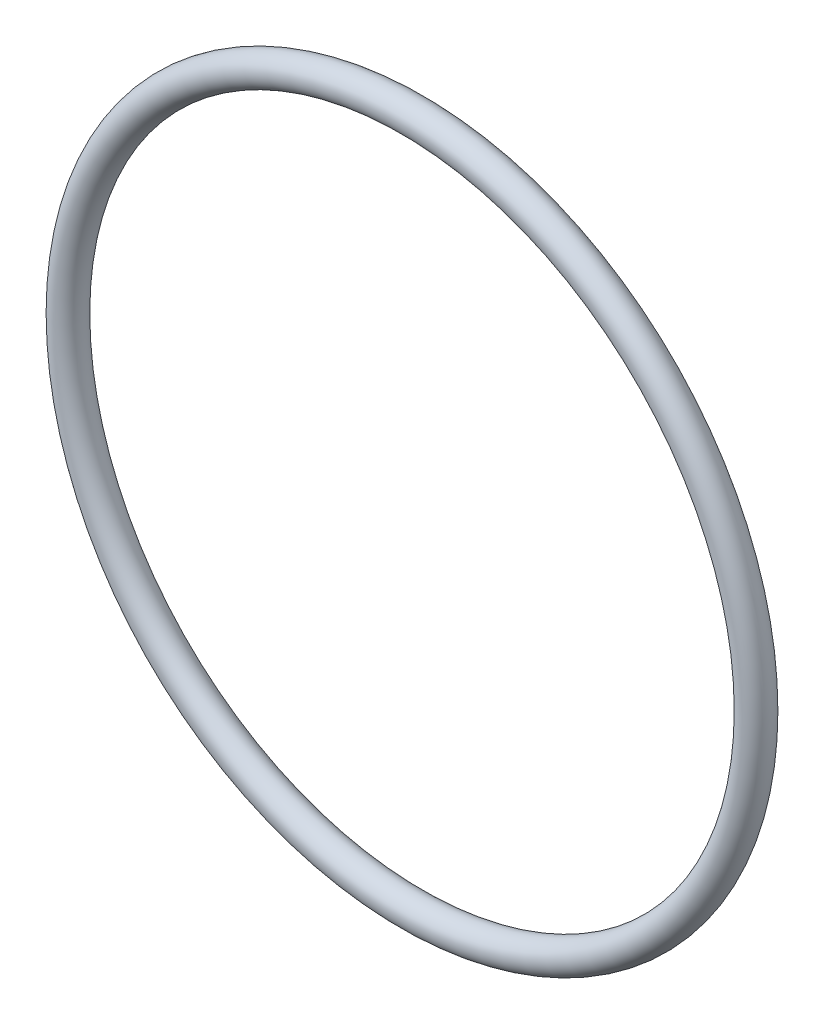
SolidWorks part; units mm, degrees
ref_plane "Front" through (0, 0, 0) normal (0, 0, 1) x (1, 0, 0)
ref_plane "Top" through (0, 0, 0) normal (0, 1, 0) x (1, 0, 0)
ref_plane "Right" through (0, 0, 0) normal (1, 0, 0) x (0, 0, -1)
sketch "Sketch1" plane through (0, 0, 0) normal (1, 0, 0) x (0, -1, 0)
  line L0 (0, -0.889) -> (0, 0.889) construction
  line L2 (-21.7792, 0) -> (21.7792, 0) construction
  line L3 (-18.9103, 0) -> (18.9103, 0) construction
  circle A0 centre (19.7993, 0) radius 0.889
  point P2 (0, 0)
  point P9 (18.9103, 0)
  point P10 (20.6883, 0)
  point P13 (19.7993, 0.889)
  point P14 (19.7993, -0.889)
  dimension "Width" = 1.778
  dimension "ID" = 37.8206
revolve "Revolve1" add sketch "Sketch1" angle 360 about L0
sketch "Sketch2" plane through (0, 0, 0) normal (0, 0, 1) x (1, 0, 0)
  circle A0 centre (0, 0) radius 19.685 construction
  dimension "D1" = 39.37
